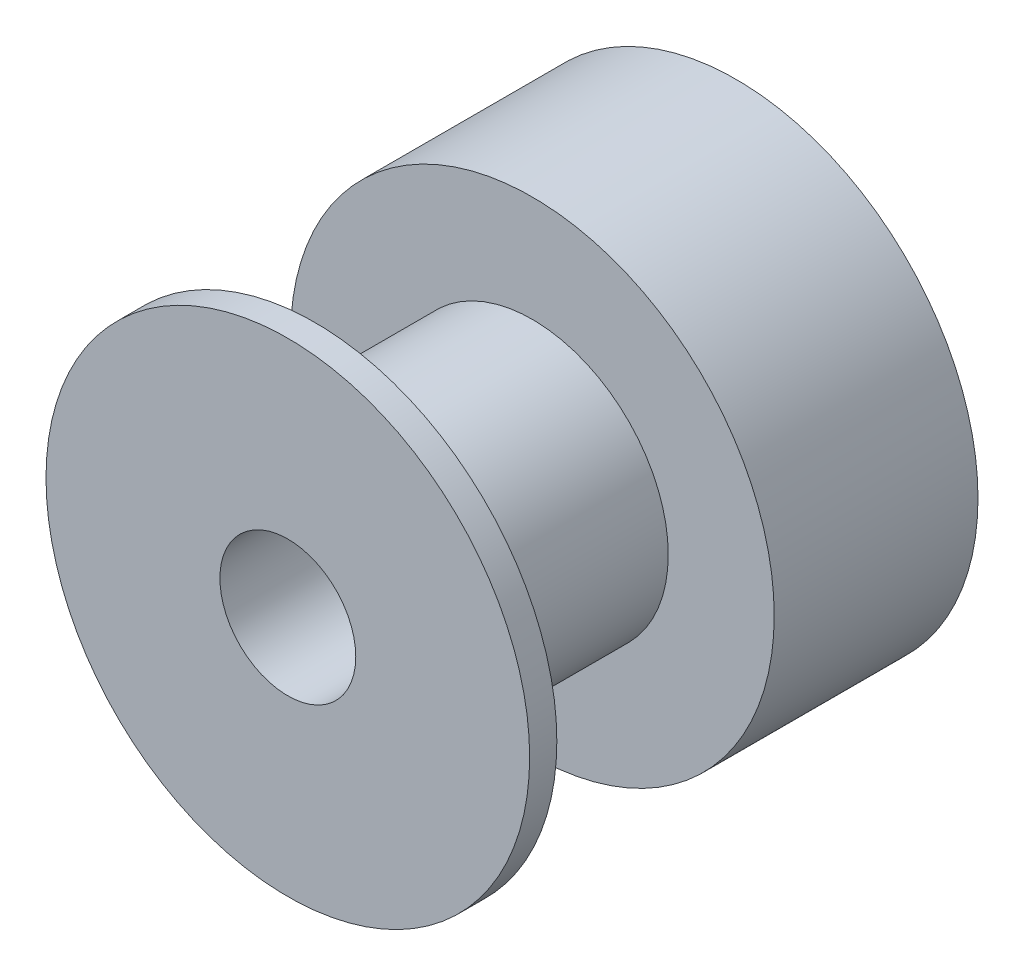
SolidWorks part; units mm, degrees
ref_plane "Front Plane" through (0, 0, 0) normal (0, 0, 1) x (1, 0, 0)
ref_plane "Top Plane" through (0, 0, 0) normal (0, 1, 0) x (1, 0, 0)
ref_plane "Right Plane" through (0, 0, 0) normal (1, 0, 0) x (0, 0, -1)
sketch "Sketch1" plane through (0, 0, 0) normal (0, 0, 1) x (1, 0, 0)
  circle A0 centre (0, 0) radius 2.5
  circle A1 centre (0, 0) radius 8.9
  dimension "D1" = 5
  dimension "D2" = 17.8
extrude "Boss-Extrude1" add sketch "Sketch1" along normal blind 16.5
sketch "Sketch2" plane through (0, 0, 16.5) normal (0, 0, 1) x (1, 0, 0)
  circle A1 centre (0, 0) radius 8.9
  circle A2 centre (0, 0) radius 8.9
  circle A4 centre (0, 0) radius 5
  circle A5 centre (0, 0) radius 5
  dimension "D1" = 0
  dimension "D2" = 2.5
extrude "Cut-Extrude1" cut sketch "Sketch2" against normal blind 8 from offset 1
